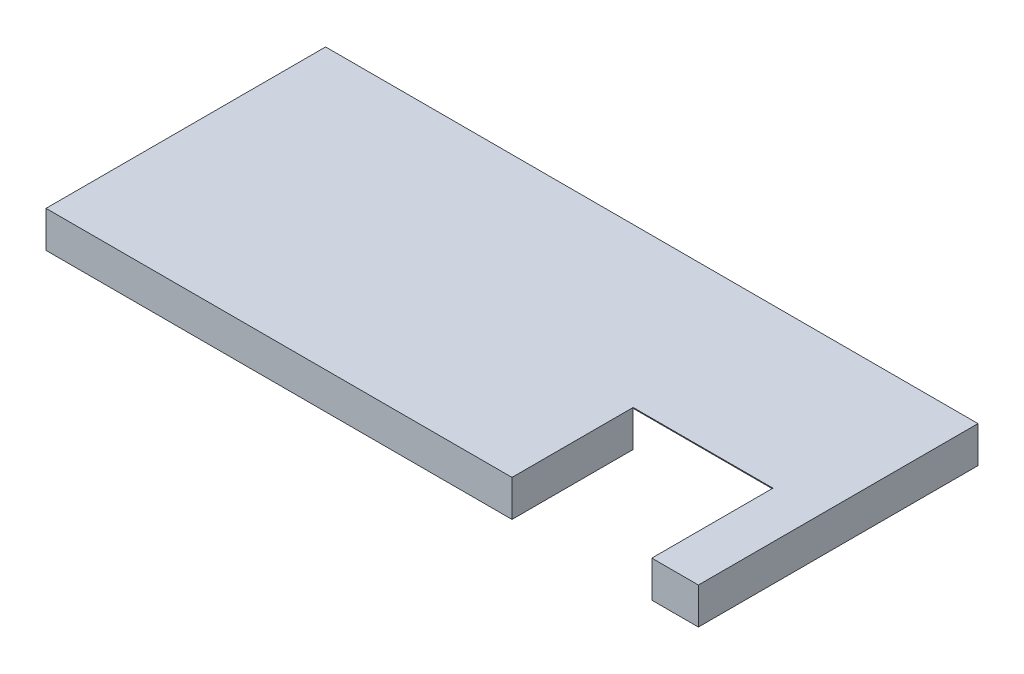
SolidWorks part; units mm, degrees
material "Balsa"
ref_plane "Front Plane" through (0, 0, 0) normal (0, 0, 1) x (1, 0, 0)
ref_plane "Top Plane" through (0, 0, 0) normal (0, 1, 0) x (1, 0, 0)
ref_plane "Right Plane" through (0, 0, 0) normal (1, 0, 0) x (0, 0, -1)
sketch "Sketch1" plane through (0, 0, 0) normal (0, 1, 0) x (1, 0, 0)
  line L1 (0, 0) -> (7000, 0)
  line L2 (0, 0) -> (0, -3000)
  line L3 (0, -3000) -> (7000, -3000)
  line L4 (7000, 0) -> (7000, -3000)
  point P0 (0, 0)
  dimension "D1" = 3000
  dimension "D2" = 7000
extrude "Boss-Extrude1" add sketch "Sketch1" along normal blind 9
sketch "Sketch3" plane through (0, 0, 0) normal (0, -1, 0) x (1, 0, 0)
  line L0 (0, 3000) -> (7000, 3000) construction
  line L1 (6500, 3000) -> (5000, 3000)
  line L2 (6500, 3000) -> (6500, 1700)
  line L3 (6500, 1700) -> (5000, 1700)
  line L4 (5000, 3000) -> (5000, 1700)
  line L5 (7000, 3000) -> (7000, 0) construction
  dimension "D1" = 1500
  dimension "D2" = 1300
  dimension "D3" = 500
extrude "Cut-Extrude1" cut sketch "Sketch3" against normal through all
sketch "Sketch4" plane through (0, 0, 0) normal (0, -1, 0) x (1, 0, 0)
  line L0 (0, 3000) -> (5000, 3000) construction
  line L1 (5000, 3000) -> (0, 3000)
  line L2 (5000, 3000) -> (5000, 2991)
  line L3 (5000, 2991) -> (0, 2991)
  line L4 (0, 3000) -> (0, 2991)
  dimension "D1" = 9
extrude "Boss-Extrude2" add sketch "Sketch4" along normal blind 382
sketch "Sketch5" plane through (0, 0, 0) normal (0, -1, 0) x (1, 0, 0)
  line L1 (0, 0) -> (9, 0)
  line L2 (0, 0) -> (0, 2991)
  line L3 (0, 2991) -> (9, 2991)
  line L4 (9, 0) -> (9, 2991)
  dimension "D1" = 9
extrude "Boss-Extrude3" add sketch "Sketch5" along normal blind 382
sketch "Sketch6" plane through (0, 0, 0) normal (0, -1, 0) x (1, 0, 0)
  line L1 (7000, 0) -> (9, 0)
  line L2 (7000, 0) -> (7000, 9)
  line L3 (7000, 9) -> (9, 9)
  line L4 (9, 0) -> (9, 9)
  dimension "D1" = 9
extrude "Boss-Extrude4" add sketch "Sketch6" along normal blind 382
sketch "Sketch7" plane through (0, 0, 0) normal (0, -1, 0) x (1, 0, 0)
  line L1 (7000, 3000) -> (6991, 3000)
  line L2 (7000, 3000) -> (7000, 9)
  line L3 (7000, 9) -> (6991, 9)
  line L4 (6991, 3000) -> (6991, 9)
  dimension "D1" = 9
extrude "Boss-Extrude5" add sketch "Sketch7" along normal blind 382
sketch "Sketch8" plane through (0, 0, 0) normal (0, -1, 0) x (1, 0, 0)
  line L0 (6500, 1700) -> (6500, 3000) construction
  line L1 (6500, 3000) -> (6991, 3000)
  line L2 (6500, 3000) -> (6500, 2991)
  line L3 (6500, 2991) -> (6991, 2991)
  line L4 (6991, 3000) -> (6991, 2991)
  dimension "D1" = 9
extrude "Boss-Extrude6" add sketch "Sketch8" along normal blind 382
sketch "Sketch9" plane through (0, 0, 0) normal (0, -1, 0) x (1, 0, 0)
  line L0 (6500, 2991) -> (6991, 2991) construction
  line L1 (6500, 1700) -> (6509, 1700)
  line L2 (6500, 1700) -> (6500, 2991)
  line L3 (6500, 2991) -> (6509, 2991)
  line L4 (6509, 1700) -> (6509, 2991)
  line L5 (6500, 1700) -> (6500, 2991) construction
  dimension "D1" = 9
extrude "Boss-Extrude7" add sketch "Sketch9" along normal blind 382
sketch "Sketch10" plane through (0, 0, 0) normal (0, -1, 0) x (1, 0, 0)
  line L1 (5000, 1700) -> (4991, 1700)
  line L2 (5000, 1700) -> (5000, 2991)
  line L3 (5000, 2991) -> (4991, 2991)
  line L4 (4991, 1700) -> (4991, 2991)
  dimension "D1" = 9
extrude "Boss-Extrude8" add sketch "Sketch10" along normal blind 382
sketch "Sketch11" plane through (0, 9, 0) normal (0, 1, 0) x (1, 0, 0)
  line L0 (0, 0) -> (0, -3000) construction
  line L1 (6991, -9) -> (4551, -9)
  line L2 (6991, -9) -> (6991, -1229)
  line L3 (6991, -1229) -> (4551, -1229)
  line L4 (4551, -9) -> (4551, -1229)
  line L5 (4551, -9) -> (2111, -9)
  line L6 (4551, -9) -> (4551, -1229)
  line L7 (4551, -1229) -> (2111, -1229)
  line L8 (2111, -9) -> (2111, -1229)
  line L9 (2111, -1229) -> (0, -1229)
  line L10 (6500, -1700) -> (6500, -1229)
  line L11 (5000, -1700) -> (5000, -1229)
  line L12 (1100, -1229) -> (3540, -1229)
  line L13 (1100, -1229) -> (1100, -2449)
  line L14 (1100, -2449) -> (3540, -2449)
  line L15 (3540, -1229) -> (3540, -2449)
  line L16 (0, -3000) -> (5000, -3000) construction
  line L17 (3540, -2449) -> (5000, -2449)
  line L18 (3540, -2449) -> (3540, -1229)
  line L19 (3540, -1229) -> (5000, -1229)
  line L20 (5000, -2449) -> (5000, -1229)
  line L21 (5000, -2449) -> (2560, -2449)
  line L22 (5000, -2449) -> (5000, -3000)
  line L23 (5000, -3000) -> (2560, -3000)
  line L24 (2560, -2449) -> (2560, -3000)
  line L26 (2560, -2449) -> (560, -2449)
  line L27 (2560, -2449) -> (2560, -3000)
  line L28 (2560, -3000) -> (560, -3000)
  line L29 (560, -2449) -> (560, -3000)
  line L30 (560, -2449) -> (0, -2449)
  line L31 (560, -2449) -> (560, -3000)
  line L32 (560, -3000) -> (0, -3000)
  line L33 (0, -2449) -> (0, -3000)
  line L34 (1100, -2449) -> (0, -2449)
  line L35 (1100, -2449) -> (1100, -1229)
  line L36 (1100, -1229) -> (0, -1229)
  line L37 (0, -2449) -> (0, -1229)
  line L38 (2111, -1229) -> (0, -1229)
  line L39 (2111, -1229) -> (2111, 0)
  line L40 (2111, 0) -> (0, 0)
  line L41 (0, -1229) -> (0, 0)
  line L42 (5000, -1229) -> (6500, -1229)
  line L43 (5000, -1229) -> (5000, -1700)
  line L44 (5000, -1700) -> (6500, -1700)
  line L45 (6500, -1229) -> (6500, -1700)
  line L46 (6991, -1229) -> (6500, -1229)
  line L47 (6991, -1229) -> (6991, -3000)
  line L48 (6991, -3000) -> (6500, -3000)
  line L49 (6500, -1229) -> (6500, -3000)
  dimension "D1" = 1220
  dimension "D2" = 2440
  dimension "D3" = 1220
  dimension "D4" = 2440
  dimension "D5" = 1220
  dimension "D6" = 2440
  dimension "D7" = 1100
  dimension "D8" = 2440
  dimension "D9" = 2000
sketch "Sketch12" plane through (0, 0, 3000) normal (0, 0, 1) x (1, 0, 0)
  line L0 (5000, -382) -> (0, -382) construction
  line L1 (5000, 9) -> (2560, 9)
  line L2 (5000, 9) -> (5000, -382)
  line L3 (5000, -382) -> (2560, -382)
  line L4 (2560, 9) -> (2560, -382)
  line L5 (1100, 9) -> (0, 9) construction
  line L6 (2560, -382) -> (1060, -382)
  line L7 (2560, -382) -> (2560, 9)
  line L8 (2560, 9) -> (1060, 9)
  line L9 (1060, -382) -> (1060, 9)
  line L11 (1060, -382) -> (0, -382)
  line L12 (1060, -382) -> (1060, 0)
  line L13 (1060, 0) -> (0, 0)
  line L14 (0, -382) -> (0, 0)
  dimension "D1" = 2440
  dimension "D2" = 1500
sketch "Sketch13" plane through (7000, 0, 0) normal (1, 0, 0) x (0, 0, -1)
  line L0 (0, -382) -> (-3000, -382) construction
  line L1 (0, 0) -> (-1500, 0)
  line L2 (0, 0) -> (0, -382)
  line L3 (0, -382) -> (-1500, -382)
  line L4 (-1500, 0) -> (-1500, -382)
  line L6 (-1500, -382) -> (-3000, -382)
  line L7 (-1500, -382) -> (-1500, 9)
  line L8 (-1500, 9) -> (-3000, 9)
  line L9 (-3000, -382) -> (-3000, 9)
sketch "Sketch14" plane through (0, 0, 0) normal (0, 0, -1) x (-1, 0, 0)
  line L0 (-5000, -382) -> (-2560, -382) construction
  line L1 (-7000, 9) -> (-4560, 9)
  line L2 (-7000, 9) -> (-7000, -382)
  line L3 (-7000, -382) -> (-4560, -382)
  line L4 (-4560, 9) -> (-4560, -382)
  line L5 (-2560, 9) -> (-560, 9) construction
  line L6 (-4560, -382) -> (-2120, -382)
  line L7 (-4560, -382) -> (-4560, 9)
  line L8 (-4560, 9) -> (-2120, 9)
  line L9 (-2120, -382) -> (-2120, 9)
  line L11 (0, 9) -> (-2120, 9)
  line L12 (0, 9) -> (0, -382)
  line L13 (0, -382) -> (-2120, -382)
  line L14 (-2120, 9) -> (-2120, -382)
  dimension "D1" = 2440
  dimension "D2" = 2440
  dimension "D3" = 2120
